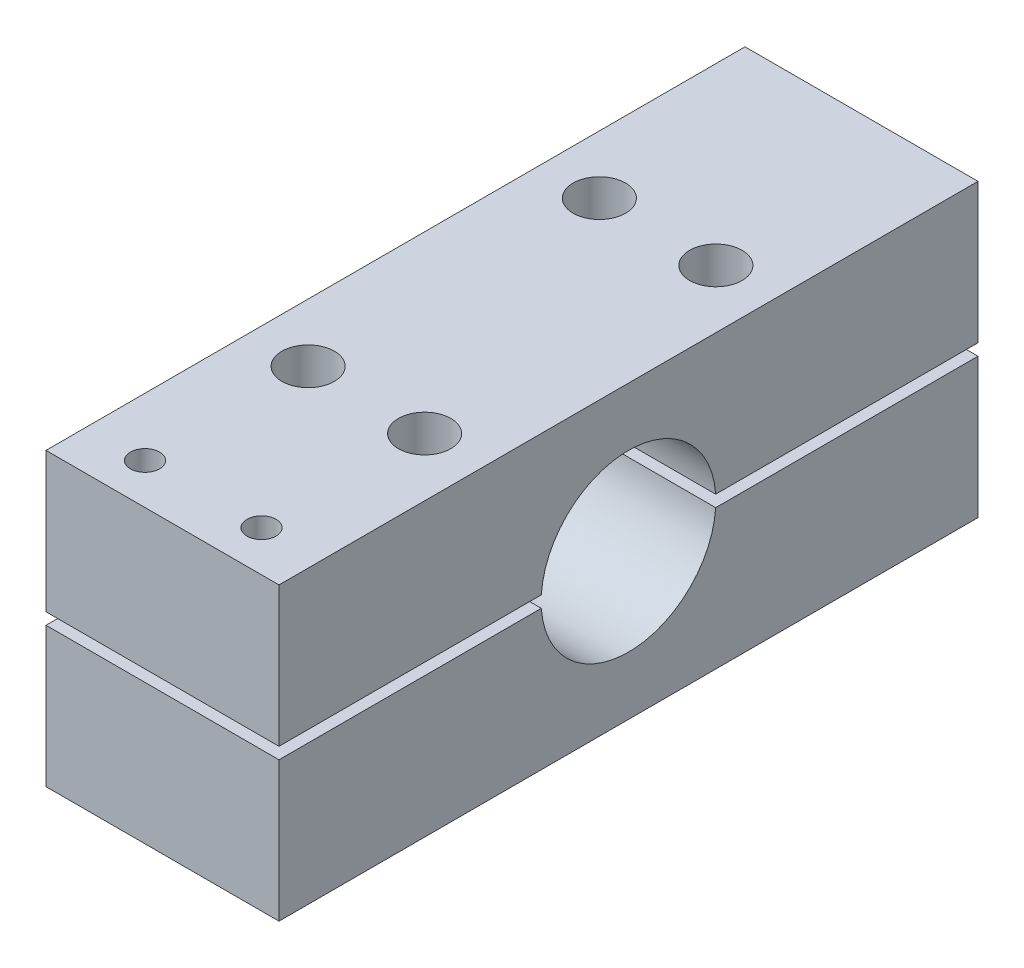
SolidWorks part; units mm, degrees
material "1.4301 (X5CrNi18-10)"
ref_plane "Vorne" through (0, 0, 0) normal (0, 0, 1) x (1, 0, 0)
ref_plane "Oben" through (0, 0, 0) normal (0, 1, 0) x (1, 0, 0)
ref_plane "Rechts" through (0, 0, 0) normal (1, 0, 0) x (0, 0, -1)
sketch "Skizze1" plane through (0, 0, 0) normal (1, 0, 0) x (0, 0, -1)
  line L1 (-60, 25) -> (60, 25)
  line L2 (-60, 25) -> (-60, -25)
  line L3 (-60, -25) -> (60, -25)
  line L4 (60, 25) -> (60, -25)
  line L5 (-60, 25) -> (60, -25) construction
  line L6 (-60, -25) -> (60, 25) construction
  circle A0 centre (0, 0) radius 15
  point P0 (0, 0)
  dimension "D1" = 30
  dimension "D2" = 120
  dimension "D3" = 50
extrude "Aufsatz-Linear austragen1" add sketch "Skizze1" along normal mid plane 40
sketch "Skizze2" plane through (20, 0, 0) normal (1, 0, 0) x (0, 0, -1)
  line L0 (60, -25) -> (60, 25) construction
  line L1 (-60, -1) -> (60, -1)
  line L2 (-60, -1) -> (-60, 1)
  line L3 (-60, 1) -> (60, 1)
  line L4 (60, -1) -> (60, 1)
  line L5 (-60, -1) -> (60, 1) construction
  line L6 (-60, 1) -> (60, -1) construction
  point P0 (0, 0)
  dimension "D1" = 2
extrude "Schnitt-Linear austragen1" cut sketch "Skizze2" against normal through all
hole_wizard "M8 Gewindebohrung1" positions "Skizze4" profile "Skizze3" tap size "M8" standard "Gabler-Normteile" end condition through all
sketch "Skizze4" plane through (0, -1, 0) normal (0, 1, 0) x (1, 0, 0)
  line L0 (-10, 25) -> (-10, -25) construction
  line L1 (-10, -25) -> (10, -25) construction
  line L2 (10, -25) -> (10, 25) construction
  line L3 (10, 25) -> (-10, 25) construction
  point P0 (10, -25)
  point P2 (10, 25)
  point P8 (-10, 25)
  point P10 (-10, -25)
  point P24 (0, 25)
  point P26 (-10, 0)
  dimension "D1" = 20
  dimension "D2" = 50
cosmetic thread "Bohrungsgewinde1" parameters "D2"=8
cosmetic thread "Bohrungsgewinde2" parameters "D2"=8
cosmetic thread "Bohrungsgewinde3" parameters "D2"=8
cosmetic thread "Bohrungsgewinde4" parameters "D2"=8
sketch "Skizze3" plane through (10, -1, 25) normal (1, 0, 0) x (0, 0, 1)
  line L0 (0, 0) -> (0, 24)
  line L1 (0, 24) -> (3.4, 24)
  line L2 (3.4, 24) -> (3.4, 0)
  line L5 (3.4, 0) -> (0, 0)
  line L11 (0, -6.35) -> (0, 107.95) construction
  dimension "Bohrerdurchmesser" = 6.8
  dimension "Bohrungstiefe" = 24
hole_wizard "Ø9.0 (9) Durchmesser Bohrung1" positions "Skizze6" profile "Skizze5" hole size "Ø9.0" standard "Gabler-Normteile"
sketch "Skizze6" plane through (0, 25, 0) normal (0, 1, 0) x (1, 0, 0)
  line L0 (10, 25) -> (-10, 25) construction
  line L1 (-10, 25) -> (-10, -25) construction
  line L2 (-10, -25) -> (10, -25) construction
  line L3 (10, -25) -> (10, 25) construction
  circle A0 centre (-10, 25) radius 3.4 construction
  circle A1 centre (10, -25) radius 3.4 construction
  point P0 (-10, -25)
  point P2 (-10, 25)
  point P8 (10, 25)
  point P10 (10, -25)
sketch "Skizze5" plane through (-10, 25, 25) normal (1, 0, 0) x (0, 0, 1)
  line L0 (0, 0) -> (0, 27.7039)
  line L1 (0, 27.7039) -> (4.5, 25)
  line L2 (4.5, 25) -> (4.5, 0)
  line L5 (4.5, 0) -> (0, 0)
  line L10 (0, 27.7039) -> (-4.5, 25) construction
  line L11 (0, -6.35) -> (0, 107.95) construction
  dimension "Bohrerdurchmesser" = 9
  dimension "Bohrungstiefe" = 25
  dimension "Spitzenwinkel" = 118
hole_wizard "Stirnsenkung für M10 Zylinderschraube mit Innensechskant2" positions "Skizze8" profile "Skizze7" counterbore size "M10" standard "Gabler-Normteile" end condition through all
sketch "Skizze8" plane through (0, -1, 0) normal (0, 1, 0) x (1, 0, 0)
  line L0 (-20, 0) -> (20, 0) construction
  line L2 (20, -60) -> (20, 60) construction
  line L3 (-20, -60) -> (-20, 60) construction
  line L4 (-20, -60) -> (20, -60) construction
  point P0 (0, -45)
  point P2 (0, 45)
  point P20 (0, -60)
  dimension "D1" = 90
sketch "Skizze7" plane through (0, -1, 45) normal (1, 0, 0) x (0, 0, 1)
  line L0 (0, 0) -> (0, 24)
  line L1 (0, 24) -> (5.5, 24)
  line L3 (5.5, 24) -> (5.5, 10.6)
  line L4 (5.5, 10.6) -> (9, 10.6)
  line L5 (9, 10.6) -> (9, 0)
  line L7 (9, 0) -> (0, 0)
  line L11 (0, -6.35) -> (0, 107.95) construction
  dimension "Bohrerdurchmesser" = 11
  dimension "Bohrungstiefe" = 24
  dimension "Senkdurchmesser2" = 18
  dimension "Senktiefe2" = 10.6
hole_wizard "M6 Gewindebohrung1" positions "Skizze10" profile "Skizze9" tap size "M6" standard "Gabler-Normteile"
sketch "Skizze10" plane through (0, 25, 0) normal (0, 1, 0) x (1, 0, 0)
  line L0 (-10, 25) -> (-10, -53) construction
  line L1 (10, 25) -> (10, -53) construction
  line L3 (20, -60) -> (-20, -60) construction
  point P0 (-10, -53)
  point P2 (10, -53)
  dimension "D1" = 7
sketch "Skizze9" plane through (-10, 25, 53) normal (1, 0, 0) x (0, 0, 1)
  line L0 (0, 0) -> (0, 18.5022)
  line L1 (0, 18.5022) -> (2.5, 17)
  line L2 (2.5, 17) -> (2.5, 0)
  line L5 (2.5, 0) -> (0, 0)
  line L10 (0, 18.5022) -> (-2.5, 17) construction
  line L11 (0, -6.35) -> (0, 107.95) construction
  dimension "Bohrerdurchmesser" = 5
  dimension "Bohrungstiefe" = 17
  dimension "Spitzenwinkel" = 118
cosmetic thread "Bohrungsgewinde5" parameters "D1"=12, "D2"=6
cosmetic thread "Bohrungsgewinde6" parameters "D1"=12, "D2"=6
